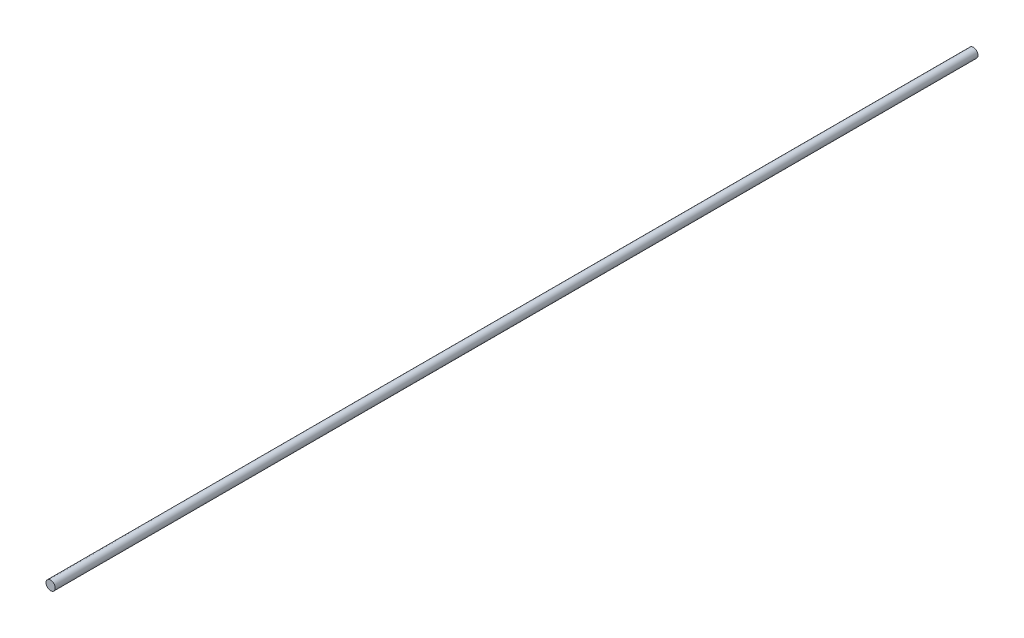
SolidWorks part; units mm, degrees
ref_plane "Plan de face" through (0, 0, 0) normal (0, 0, 1) x (1, 0, 0)
ref_plane "Plan de dessus" through (0, 0, 0) normal (0, 1, 0) x (1, 0, 0)
ref_plane "Plan de droite" through (0, 0, 0) normal (1, 0, 0) x (0, 0, -1)
sketch "Esquisse1" plane through (0, 0, 0) normal (0, 0, 1) x (1, 0, 0)
  circle A0 centre (0, 0) radius 5
  dimension "D1" = 10
extrude "Boss.-Extru.1" add sketch "Esquisse1" along normal blind 1000
